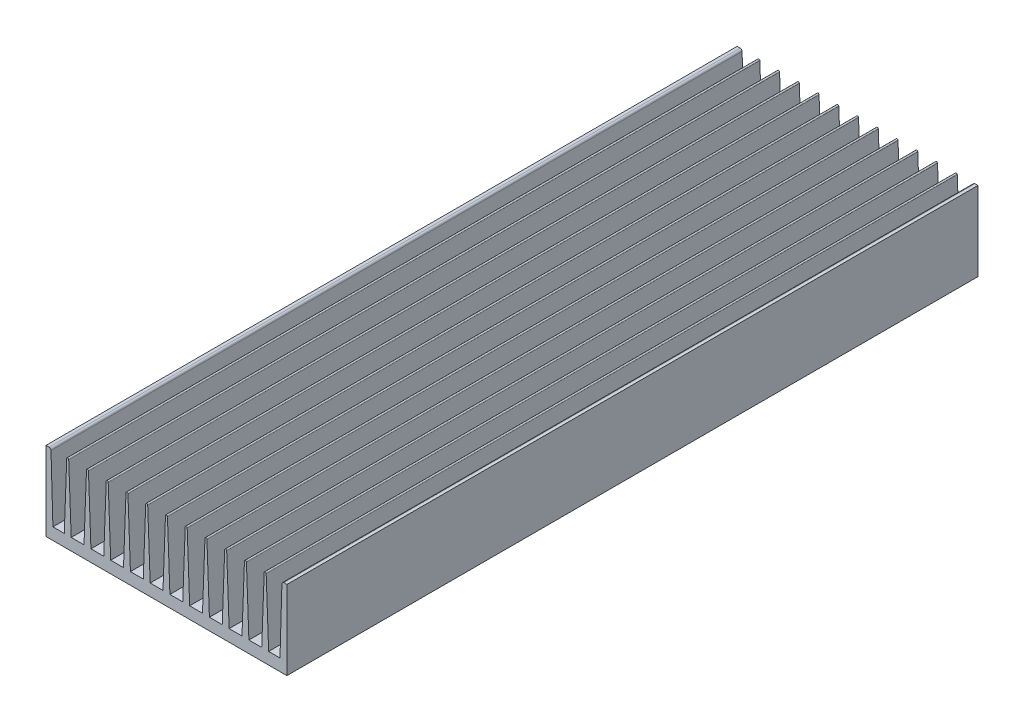
SolidWorks part; units mm, degrees
ref_plane "Спереди" through (0, 0, 0) normal (0, 0, 1) x (1, 0, 0)
ref_plane "Сверху" through (0, 0, 0) normal (0, 1, 0) x (1, 0, 0)
ref_plane "Справа" through (0, 0, 0) normal (1, 0, 0) x (0, 0, -1)
sketch "Эскиз1" plane through (0, 0, 0) normal (0, 0, 1) x (1, 0, 0)
  line L0 (0, 40) -> (1.529, 40)
  line L1 (0, 0) -> (122, 0)
  line L2 (2.5285, 39.0294) -> (3.5, 6)
  line L3 (0, 40) -> (0, 0)
  line L4 (122, 40) -> (122, 0)
  line L5 (61, 63.7127) -> (61, -22.2582) construction
  line L8 (122, 40) -> (120.471, 40)
  line L9 (119.4715, 39.0294) -> (118.5, 6)
  line L10 (3.5, 6) -> (118.5, 6)
  arc A0 (1.529, 40) -> (2.5285, 39.0294) centre (1.529, 39) cw
  arc A2 (120.471, 40) -> (119.4715, 39.0294) centre (120.471, 39) ccw
  point P18 (119.5, 40)
  dimension "D9" = 1
  dimension "D1" = 122
  dimension "D2" = 6
  dimension "D3" = 40
  dimension "D4" = 3.5
  dimension "D7" = 2.5
extrude "Вытянуть1" add sketch "Эскиз1" along normal blind 350
sketch "Эскиз2" plane through (0, 0, 350) normal (0, 0, 1) x (1, 0, 0)
  line L0 (118.5, 6) -> (3.5, 6) construction
  line L1 (10.5, 39.5) -> (9.25, 6)
  line L2 (11, 39.5) -> (11, 22.5548) construction
  line L3 (11.5, 39.5) -> (12.75, 6)
  line L4 (9.25, 6) -> (12.75, 6)
  line L6 (0, 40) -> (0, 0) construction
  arc A0 (10.5, 39.5) -> (11.5, 39.5) centre (11, 39.5) cw
  dimension "D1" = 34
  dimension "D3" = 0.5
  dimension "D2" = 3.5
  dimension "D4" = 11
  dimension "D5" = 1
extrude "Вытянуть3" add sketch "Эскиз2" against normal blind 350
pattern_curve "Кривая1" of "Вытянуть3" along edge at (61, 0, 0) parameters "D1"=11, "D3"=10, "D2"=1, "D4"=50
sketch "Эскиз3" plane through (0, 0, 0) normal (0, -1, 0) x (1, 0, 0)
  line L0 (-14.0506, 342) -> (137.5079, 342) construction
  line L1 (0, 350) -> (122, 350) construction
  line L2 (0, 350) -> (0, 0) construction
  line L3 (-46.7511, 175) -> (151.4312, 175) construction
  line L4 (0, 0) -> (122, 0) construction
  circle A0 centre (26, 342) radius 2.25
  circle A1 centre (96, 342) radius 2.25
  circle A2 centre (96, 8) radius 2.25
  circle A3 centre (26, 8) radius 2.25
  dimension "D2" = 70
  dimension "D4" = 4.5
  dimension "D1" = 8
  dimension "D3" = 26
extrude "Вырез-Вытянуть1" cut sketch "Эскиз3" against normal blind 6
sketch "Эскиз4" plane through (0, 0, 0) normal (0, -1, 0) x (1, 0, 0)
  line L0 (12.5, 40) -> (12.5, 92) construction
  line L1 (122, 350) -> (122, 0) construction
  line L2 (0, 0) -> (122, 0) construction
  line L3 (32, 25) -> (32, 91) construction
  line L4 (32, 25) -> (80, 25) construction
  line L5 (80, 25) -> (80, 91) construction
  line L6 (80, 91) -> (32, 91) construction
  line L7 (37.5, 115) -> (37.5, 255) construction
  line L8 (72, 128) -> (72, 195) construction
  line L9 (26, 295) -> (26, 320) construction
  line L10 (0, 350) -> (0, 0) construction
  circle A0 centre (12.5, 40) radius 2.25
  circle A1 centre (12.5, 92) radius 2.25
  circle A2 centre (32, 25) radius 1.6
  circle A3 centre (80, 25) radius 1.6
  circle A4 centre (80, 91) radius 1.6
  circle A5 centre (32, 91) radius 1.6
  circle A6 centre (37.5, 115) radius 1.6
  circle A7 centre (37.5, 255) radius 1.6
  circle A8 centre (72, 128) radius 1.6
  circle A9 centre (72, 195) radius 1.6
  circle A10 centre (26, 295) radius 2.25
  circle A11 centre (26, 320) radius 2.25
  dimension "D2" = 40
  dimension "D4" = 4.5
  dimension "D5" = 42
  dimension "D6" = 48
  dimension "D9" = 3.2
  dimension "D15" = 195
  dimension "D17" = 320
  dimension "D18" = 295
  dimension "D19" = 4.5
  dimension "D20" = 12.5
  dimension "D3" = 52
  dimension "D7" = 25
  dimension "D8" = 66
  dimension "D10" = 37.5
  dimension "D11" = 115
  dimension "D12" = 255
  dimension "D13" = 50
  dimension "D14" = 128
  dimension "D16" = 26
extrude "Вырез-Вытянуть2" cut sketch "Эскиз4" against normal blind 6
cosmetic thread "Условное изображение резьбы1" parameters "D1"=6, "D2"=4
cosmetic thread "Условное изображение резьбы2" parameters "D1"=6, "D2"=4
cosmetic thread "Условное изображение резьбы3" parameters "D1"=6, "D2"=4
cosmetic thread "Условное изображение резьбы4" parameters "D1"=6, "D2"=4
cosmetic thread "Условное изображение резьбы5" parameters "D1"=6, "D2"=4
cosmetic thread "Условное изображение резьбы6" parameters "D1"=6, "D2"=4
cosmetic thread "Условное изображение резьбы7" parameters "D1"=6, "D2"=4
cosmetic thread "Условное изображение резьбы8" parameters "D1"=6, "D2"=4
